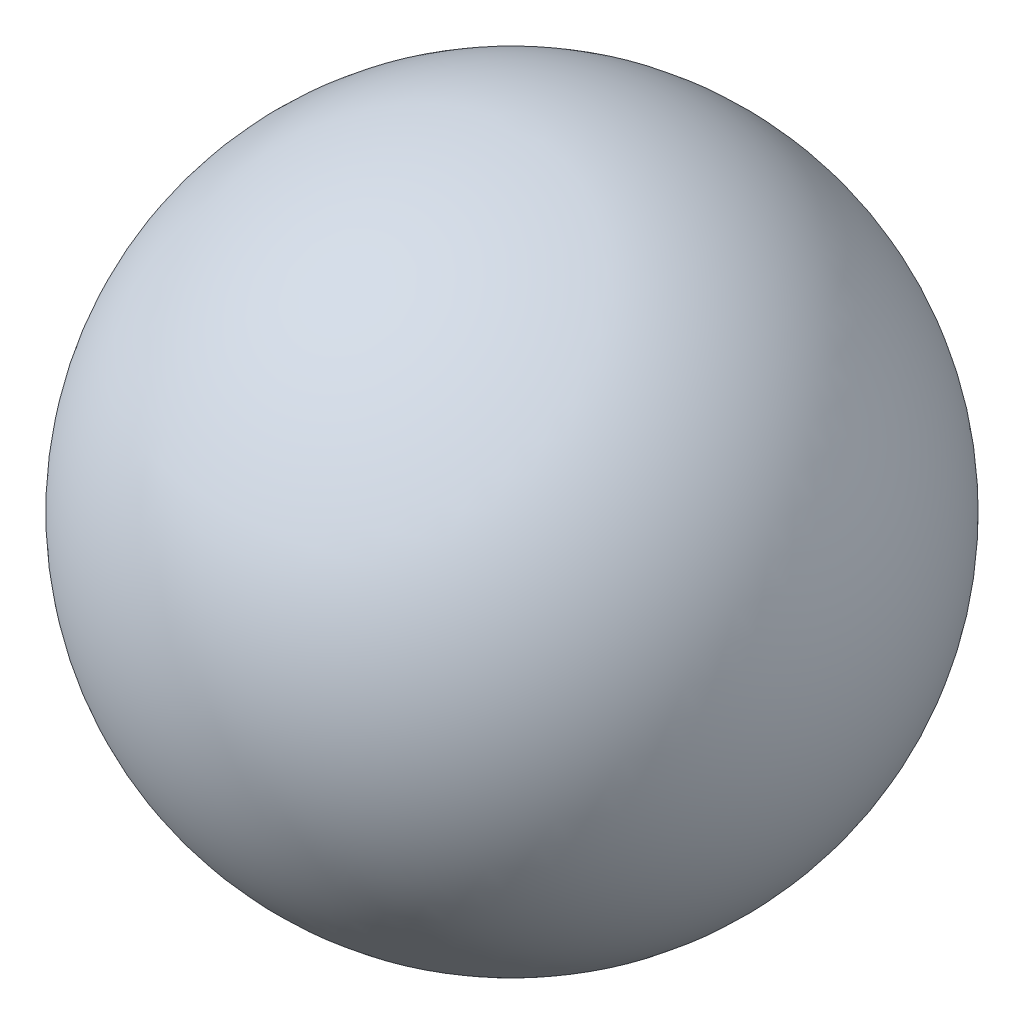
SolidWorks part; units mm, degrees
ref_plane "Front Plane" through (0, 0, 0) normal (0, 0, 1) x (1, 0, 0)
ref_plane "Top Plane" through (0, 0, 0) normal (0, 1, 0) x (1, 0, 0)
ref_plane "Right Plane" through (0, 0, 0) normal (1, 0, 0) x (0, 0, -1)
sketch "Sketch1" plane through (0, 0, 0) normal (0, 0, 1) x (1, 0, 0)
  line L0 (0, 0) -> (0, 431.8) construction
  line L1 (0, -110.1591) -> (0, 110.1591)
  arc A1 (0, -110.1591) -> (0, 110.1591) centre (0, 0) ccw
  dimension "D1" = 110.1591
revolve "Revolve1" add sketch "Sketch1" angle 360 about L0
